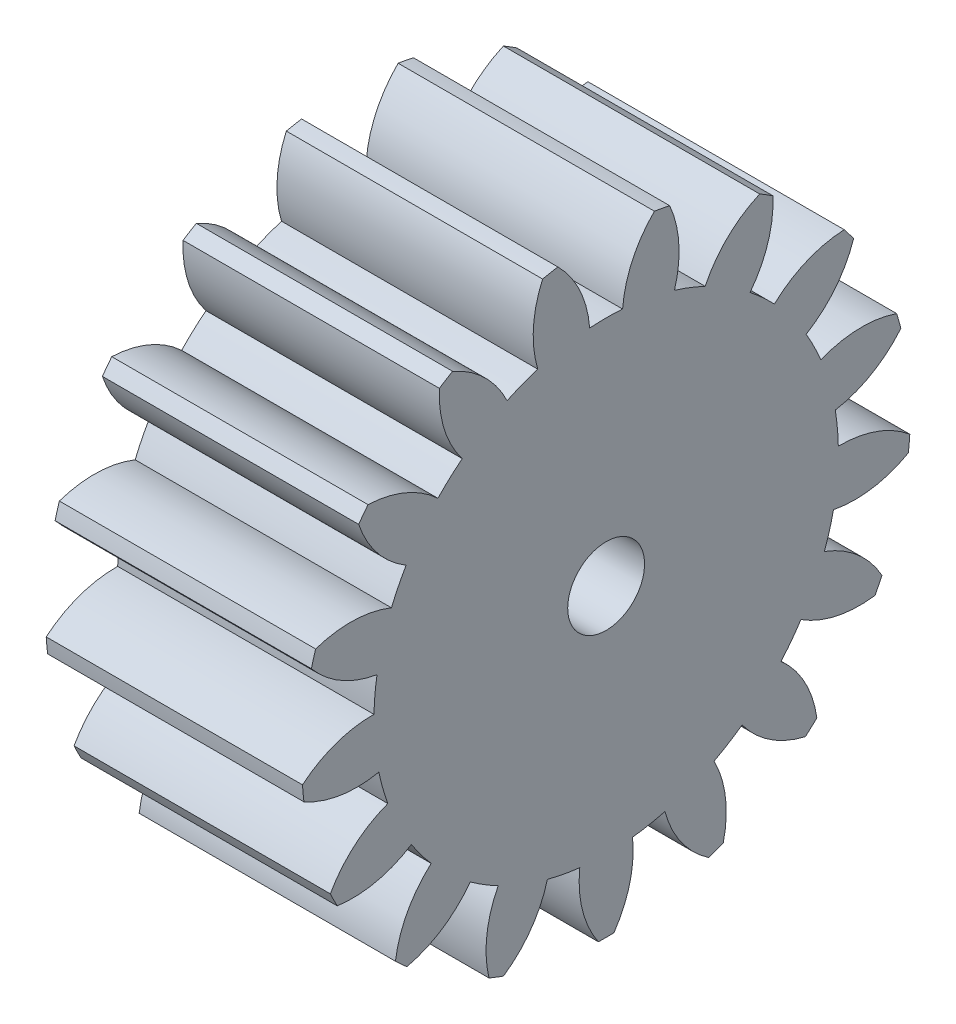
SolidWorks part; units mm, degrees
ref_plane "Plane1" through (0, 0, 0) normal (0, 0, 1) x (1, 0, 0)
ref_plane "Plane2" through (0, 0, 0) normal (0, 1, 0) x (1, 0, 0)
ref_plane "Plane3" through (0, 0, 0) normal (1, 0, 0) x (0, 0, -1)
sketch "HoldingSke" plane through (0, 0, 0) normal (0, 1, 0) x (1, 0, 0)
  line L0 (0, 0) -> (0.765, -0.2339)
  line L1 (-15, 0) -> (100, 0) construction
  line L2 (0, 0) -> (-2.1039, 2.3779)
  line L3 (0, 0) -> (-11.863, 4.5341)
  line L4 (0, 0) -> (8.2586, 2.5249)
  line L5 (0, 0) -> (-46.8476, -17.4728)
  line L6 (0, 0) -> (-8.2896, -5.593)
  line L7 (-2.1039, 2.3779) -> (8.6586, 51.2059)
  line L8 (-76.2, 54.61) -> (-75.7, 54.61)
  line L9 (-71.009, 38.7566) -> (-53.1078, 45.2721)
  line L10 (-76.2, 71.12) -> (104.1128, 71.12)
  line L11 (0, 0) -> (-10, 0)
  line L12 (-76.2, 101.6) -> (-76.155, 101.6)
  line L13 (24.9733, 27.94) -> (52.9518, 28.4284)
  line L14 (24.9733, 27.94) -> (24.9743, 27.94)
  line L15 (24.9733, 27.94) -> (100.4006, 29.5858)
  line L16 (-63.627, -1.25) -> (-12.827, -1.25)
  circle A0 centre (0, 0) radius 1.5
  circle A1 centre (0, 0) radius 9.0615
  circle A2 centre (0, 0) radius 37.5
  circle A3 centre (0, 0) radius 1.5
  dimension "MHD" = 18.123
  dimension "Hub_dia" = 75
  dimension "Bore" = 3
  dimension "MBD" = 3
  dimension "Num_teeth" = 17
  dimension "Pitch" = 0.8
  dimension "Overall_len" = 50
  dimension "Show_teeth" = 17
  dimension "Thickness" = 10
  dimension "OAL" = 50.0001
  dimension "T_dim" = 0.5
  dimension "Ap" = 20
  dimension "H" = 19.05
  dimension "Pitch_radius" = 180.3128
  dimension "Width" = 10
  dimension "Backlash" = 0.045
  dimension "Addendum_fac" = 1
  dimension "Dedendum_fac" = 1.25
  dimension "Clearance_fac" = 0.25
  dimension "Dedendum_add" = 0.001
  dimension "Module" = 1.25
sketch "BasProSke" plane through (0, 0, 0) normal (0, 1, 0) x (1, 0, 0)
  line L0 (-10, 0) -> (60, 0) construction
  line L1 (0, 0) -> (0, 11.875)
  line L2 (0, 0) -> (10, 0)
  line L3 (10, 0) -> (10, 11.875)
  line L4 (10, 11.875) -> (0, 11.875)
  dimension "Thickness" = 10
  dimension "Diameter" = 23.75
revolve "Base-Revolve" add sketch "BasProSke" angle 360 about L0
sketch "TooCutSke" plane through (0, 0, 0) normal (1, 0, 0) x (0, 0, -1)
  line L1 (0, 0) -> (0, 107) construction
  line L2 (0, 0) -> (-1.059, 10.5721) construction
  line L3 (0, 0) -> (-3.8906, 20.8128) construction
  line L4 (-1.059, 10.5721) -> (-1.9453, 10.4064) construction
  arc A0 (0.6424, 9.0387) -> (-0.6424, 9.0387) centre (0, 0) ccw
  arc A1 (1.9058, 11.7468) -> (-1.9058, 11.7468) centre (0, 0) ccw
  circle A2 centre (0, 0) radius 10.625 construction
  circle A3 centre (0, 0) radius 9.9842 construction
  arc A4 (-0.6424, 9.0387) -> (-1.9058, 11.7468) centre (-4.8797, 8.7106) ccw
  arc A5 (1.9058, 11.7468) -> (0.6424, 9.0387) centre (4.8797, 8.7106) ccw
  dimension "Root_dia" = 18.123
  dimension "Overcut_dia" = 23.8008
  dimension "Pitch_dia" = 21.25
  dimension "Base_dia" = 19.9685
  dimension "Flank_rad" = 4.25
  dimension "Half_ang" = 10.588
  dimension "Half_CT" = 0.9016
extrude "ToothCut" cut sketch "TooCutSke" along normal through all
fillet "Breaks" [suppressed] radius 0.025
fillet "RootFillets" [suppressed] radius 0.3135
pattern_circular "TeethCuts" count 17 every 21.176 about axis through (-10, 0, 0) along (1, 0, 0) of "ToothCut", "RootFillets", "Breaks"
sketch "HubNeaOneSke" plane through (0, 0, 0) normal (-1, 0, 0) x (0, 0, 1)
  circle A0 centre (0, 0) radius 9.0615
  dimension "Diameter" = 18.123
extrude "HubNearOne" [suppressed] add sketch "HubNeaOneSke" along normal blind 40.0001
sketch "HubNeaBotSke" plane through (0, 0, 0) normal (-1, 0, 0) x (0, 0, 1)
  circle A0 centre (0, 0) radius 9.0615
  dimension "Diameter" = 18.123
extrude "HubNearBoth" [suppressed] add sketch "HubNeaBotSke" along normal blind 20
ref_plane "FarPln" through (10, 0, 0) normal (1, 0, 0) x (0, 0, -1)
sketch "HubFarSke" plane through (10, 0, 0) normal (1, 0, 0) x (0, 0, -1)
  circle A0 centre (0, 0) radius 9.0615
  dimension "Diameter" = 18.123
extrude "HubFar" [suppressed] add sketch "HubFarSke" along normal blind 20
sketch "BorSke" plane through (0, 0, 0) normal (1, 0, 0) x (0, 0, -1)
  circle A0 centre (0, 0) radius 1.5
  dimension "Diameter" = 3
extrude "Bore" cut sketch "BorSke" along normal mid plane 100.0001
sketch "KeySke" plane through (0, 0, 0) normal (1, 0, 0) x (0, 0, -1)
  line L0 (-0.6, 0) -> (-0.6, 2)
  line L1 (-0.6, 2) -> (0.6, 2)
  line L2 (0.6, 2) -> (0.6, 0)
  line L3 (0, 0) -> (0, 34) construction
  line L4 (-0.6, 0) -> (0.6, 0)
  dimension "Offset" = 2
  dimension "Width" = 1.2
extrude "Keyway" [suppressed] cut sketch "KeySke" along normal mid plane 100.0001
pattern_circular "Keyway2" [suppressed] count 2 every 90 about axis through (-10, 0, 0) along (1, 0, 0)
equation "' \"Module@HoldingSke\" = 6.35"
equation "' \"Num_teeth@HoldingSke\" = 12"
equation "' \"Ap@HoldingSke\" =  20"
equation "' \"Ap@HoldingSke\" = 20"
equation "' \"Width@HoldingSke\" = 0.5 * 25.4"
equation "' \"Hub_dia@HoldingSke\"= 1 * 25.4"
equation "' \"Hub_dia@HoldingSke\" = 1 * 25.4"
equation "' \"Overall_len@HoldingSke\" = 1.0 * 25.4"
equation "' \"Bore@HoldingSke\" = 0.75 * 25.4"
equation "' \"T_dim@HoldingSke\" = 0.1 * 25.4"
equation "' \"Width@KeySke\" = 0.25 * 25.4"
equation "' \"Show_teeth@HoldingSke\" = 13"
equation "' \"Backlash@HoldingSke\" = 0.009 * 25.4"
equation "' \"Addendum_fac@HoldingSke\" = 1.0"
equation "' \"Dedendum_fac@HoldingSke\" = 1.25"
equation "' \"Dedendum_add@HoldingSke\" = 0.00005 * 25.4"
equation "' \"Clearance_fac@HoldingSke\" = 0.25"
equation "\"Pitch@HoldingSke\" = 1 / \"Module@HoldingSke\""
equation "\"Overcut_dia@TooCutSke\" = (\"Num_teeth@HoldingSke\" + 2 * \"Addendum_fac@HoldingSke\") / \"Pitch@HoldingSke\" + 0.002 * 25.4"
equation "\"Pitch_dia@TooCutSke\" = \"Num_teeth@HoldingSke\" / \"Pitch@HoldingSke\""
equation "\"Base_dia@TooCutSke\" = \"Num_teeth@HoldingSke\" / \"Pitch@HoldingSke\" * cos((\"Ap@HoldingSke\"  * 3.14159265 / 180))"
equation "\"Root_dia@TooCutSke\" = (\"Num_teeth@HoldingSke\" + 2) / \"Pitch@HoldingSke\" - 2 * (\"Addendum_fac@HoldingSke\" + \"Dedendum_fac@HoldingSke\") / \"Pitch@HoldingSke\" - \"Dedendum_add@HoldingSke\" * 2"
equation "\"Half_ang@TooCutSke\" = 180 / \"Num_teeth@HoldingSke\""
equation "\"Half_CT@TooCutSke\" = \"Num_teeth@HoldingSke\" / \"Pitch@HoldingSke\" * sin((3.14159265 / 2 / \"Num_teeth@HoldingSke\")) / 2 - 7 * \"Backlash@HoldingSke\" / 4"
equation "\"Flank_rad@TooCutSke\" = \"Num_teeth@HoldingSke\" / \"Pitch@HoldingSke\" / 5"
equation "\"Radius@RootFillets\" = \"Clearance_fac@HoldingSke\" / \"Pitch@HoldingSke\" + \"Dedendum_add@HoldingSke\""
equation "\"Break_rad@Breaks\" = 0.02 / \"Pitch@HoldingSke\""
equation "\"Thickness@HoldingSke\" = \"Width@HoldingSke\""
equation "\"OAL@HoldingSke\" = \"Thickness@HoldingSke\""
equation "\"MHD@HoldingSke\" = (\"Num_teeth@HoldingSke\" + 2) / \"Pitch@HoldingSke\" - 2 * (\"Addendum_fac@HoldingSke\" + \"Dedendum_fac@HoldingSke\")  / \"Pitch@HoldingSke\" - \"Dedendum_add@HoldingSke\" * 2"
equation "\"MBD@HoldingSke\" = (\"Num_teeth@HoldingSke\" + 2) / \"Pitch@HoldingSke\" - 2 * (\"Addendum_fac@HoldingSke\" + \"Dedendum_fac@HoldingSke\")  / \"Pitch@HoldingSke\" - \"Dedendum_add@HoldingSke\" * 2 - 0.002 * 25.4"
equation "\"MHD@HoldingSke\" = ((sgn( \"MHD@HoldingSke\" - \"Hub_dia@HoldingSke\" )-1)*( \"MHD@HoldingSke\" - \"Hub_dia@HoldingSke\" ))/-2+ \"Hub_dia@HoldingSke\""
equation "\"MBD@HoldingSke\" = ((sgn( \"MBD@HoldingSke\" - \"Bore@HoldingSke\" )-1)*( \"MBD@HoldingSke\" - \"Bore@HoldingSke\" ))/-2+ \"Bore@HoldingSke\""
equation "\"OAL@HoldingSke\" = ((sgn( \"OAL@HoldingSke\" - \"Overall_len@HoldingSke\" )+1)*( \"OAL@HoldingSke\" - \"Overall_len@HoldingSke\" ))/2 + \"Overall_len@HoldingSke\" + 0.000002 * 25.4"
equation "\"Num_teeth@TeethCuts\" = int( \"Show_teeth@HoldingSke\" ) + 1"
equation "\"Num_teeth@TeethCuts\" = ((sgn( \"Num_teeth@TeethCuts\" - \"Num_teeth@HoldingSke\" )-1)*( \"Num_teeth@TeethCuts\" - \"Num_teeth@HoldingSke\" ))/-2+ \"Num_teeth@HoldingSke\""
equation "\"Num_teeth@TeethCuts\" = ((sgn( \"Num_teeth@TeethCuts\" - 2.0)+1)*( \"Num_teeth@TeethCuts\" - 2.0))/2 +2.0"
equation "\"Angle@TeethCuts\" = 360.0 / \"Num_teeth@HoldingSke\""
equation "\"Diameter@BasProSke\" = (\"Num_teeth@HoldingSke\" + 2 * \"Addendum_fac@HoldingSke\") / \"Pitch@HoldingSke\""
equation "\"Thickness@BasProSke\"  = \"Thickness@HoldingSke\""
equation "' \"Fillet_rad@BasProSke\" =  \"Thickness@HoldingSke\" * 0.05"
equation "' \"Fillet_rad@BasProSke\" = \"Thickness@HoldingSke\" * 0.05"
equation "\"MHD@HoldingSke\" = ((sgn( \"MHD@HoldingSke\" - \"Root_dia@TooCutSke\" )-1)*( \"MHD@HoldingSke\" - \"Root_dia@TooCutSke\" ))/-2+ \"Root_dia@TooCutSke\""
equation "\"Diameter@HubNeaOneSke\" = \"MHD@HoldingSke\""
equation "\"Length@HubNearOne\" = \"OAL@HoldingSke\" - \"Thickness@BasProSke\""
equation "\"Diameter@HubNeaBotSke\" = \"MHD@HoldingSke\""
equation "\"Length@HubNearBoth\" = ( \"OAL@HoldingSke\" - \"Thickness@BasProSke\" ) / 2.0"
equation "\"Thickness@FarPln\" = \"Thickness@BasProSke\""
equation "\"Diameter@HubFarSke\" = \"MHD@HoldingSke\""
equation "\"Length@HubFar\" = ( \"OAL@HoldingSke\" - \"Thickness@BasProSke\" ) / 2.0"
equation "\"Diameter@BorSke\" = \"MBD@HoldingSke\""
equation "\"D1@Bore\" = \"OAL@HoldingSke\" * 2.0"
equation "\"D1@Keyway\" = \"OAL@HoldingSke\" * 2.0"
equation "\"Offset@KeySke\" = \"T_dim@HoldingSke\" + \"MBD@HoldingSke\" / 2.0"
